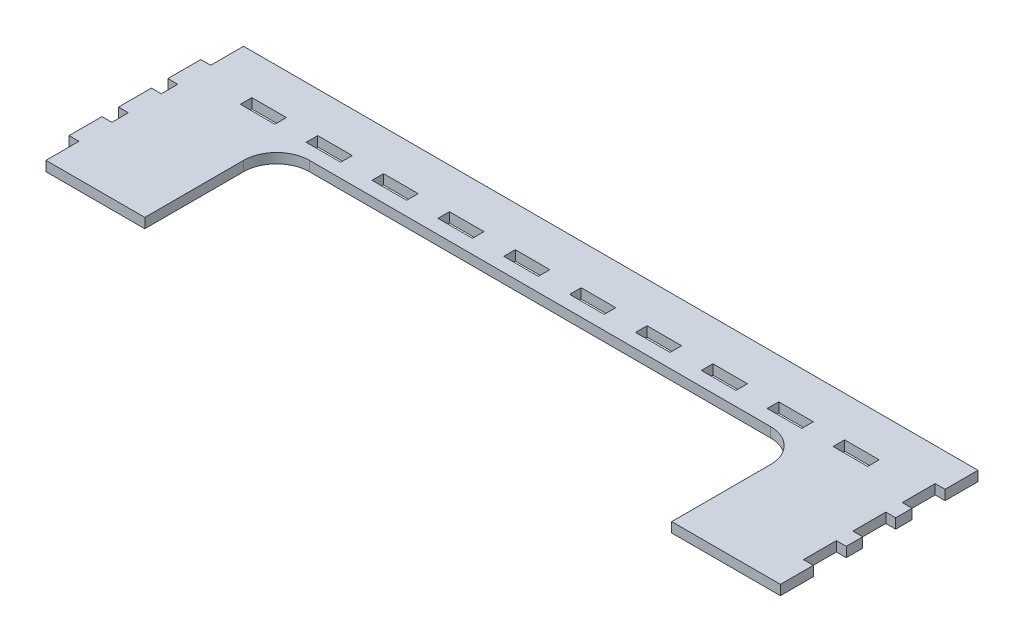
SolidWorks part; units mm, degrees
ref_plane "Спереди" through (0, 0, 0) normal (0, 0, 1) x (1, 0, 0)
ref_plane "Сверху" through (0, 0, 0) normal (0, 1, 0) x (1, 0, 0)
ref_plane "Справа" through (0, 0, 0) normal (1, 0, 0) x (0, 0, -1)
sketch "Эскиз1" plane through (0, 0, 0) normal (0, 1, 0) x (1, 0, 0)
  line L0 (-135, -31.7889) -> (-138, -31.7889)
  line L1 (45, -16.7889) -> (-95, -16.7889)
  line L3 (75, 3.2111) -> (-125, 3.2111)
  line L4 (-138, -31.7889) -> (-138, -21.7889)
  line L5 (-135, -56.7889) -> (-105, -56.7889)
  line L6 (-105, -56.7889) -> (-105, -26.7889)
  line L7 (-25, -16.7889) -> (-25, 56.3847) construction
  line L8 (85, -56.7889) -> (55, -56.7889)
  line L9 (55, -56.7889) -> (55, -26.7889)
  line L10 (88, -31.7889) -> (88, -36.7889)
  line L11 (-138, -21.7889) -> (-135, -21.7889)
  line L12 (-135, 3.2111) -> (-125, 3.2111)
  line L13 (88, -16.7889) -> (88, -21.7889)
  line L14 (85, 3.2111) -> (75, 3.2111)
  line L15 (-135, -46.7889) -> (-138, -46.7889)
  line L16 (-138, -46.7889) -> (-138, -36.7889)
  line L17 (-138, -36.7889) -> (-135, -36.7889)
  line L18 (-135, -46.7889) -> (-135, -56.7889)
  line L19 (-135, -16.7889) -> (-138, -16.7889)
  line L20 (-138, -16.7889) -> (-138, -6.7889)
  line L21 (-138, -6.7889) -> (-135, -6.7889)
  line L22 (-135, 3.2111) -> (-135, -6.7889)
  line L23 (-135, -16.7889) -> (-135, -21.7889)
  line L24 (-135, -31.7889) -> (-135, -36.7889)
  line L25 (88, -6.7889) -> (85, -6.7889)
  line L26 (85, -21.7889) -> (85, -31.7889)
  line L27 (85, -16.7889) -> (88, -16.7889)
  line L29 (88, -36.7889) -> (85, -36.7889)
  line L31 (85, -46.7889) -> (88, -46.7889)
  line L32 (88, -21.7889) -> (85, -21.7889)
  line L33 (85, -36.7889) -> (85, -46.7889)
  line L34 (85, -31.7889) -> (88, -31.7889)
  line L35 (85, 3.2111) -> (88, 3.2111)
  line L36 (88, 3.2111) -> (88, -6.7889)
  line L37 (85, -6.7889) -> (85, -16.7889)
  line L38 (88, -46.7889) -> (88, -56.7889)
  line L39 (88, -56.7889) -> (85, -56.7889)
  arc A2 (55, -26.7889) -> (45, -16.7889) centre (45, -26.7889) ccw
  arc A3 (-95, -16.7889) -> (-105, -26.7889) centre (-95, -26.7889) ccw
  point P0 (0, 0)
  point P16 (85, 3.2111)
  point P19 (-135, 3.2111)
  point P22 (55, -16.7889)
  point P25 (-105, -16.7889)
  dimension "D5" = 3
  dimension "D6" = 10
  dimension "D1" = 220
  dimension "D2" = 60
  dimension "D3" = 3
  dimension "D4" = 30
  dimension "D7" = 10
  dimension "D8" = 10
extrude "Бобышка-Вытянуть1" add sketch "Эскиз1" along normal blind 3
sketch "Эскиз2" plane through (0, 0, 0) normal (0, 1, 0) x (1, 0, 0)
  line L0 (-95, -16.7889) -> (45, -16.7889) construction
  line L1 (-105, -10.7889) -> (-44.1885, -10.7889) construction
  line L3 (-120.25, -12.5389) -> (-109.75, -12.5389)
  line L4 (-120.25, -12.5389) -> (-120.25, -9.0389)
  line L5 (-120.25, -9.0389) -> (-109.75, -9.0389)
  line L6 (-109.75, -12.5389) -> (-109.75, -9.0389)
  line L7 (-120.25, -12.5389) -> (-109.75, -9.0389) construction
  line L8 (-120.25, -9.0389) -> (-109.75, -12.5389) construction
  line L10 (-100.25, -9.0389) -> (-89.75, -9.0389)
  line L11 (-100.25, -12.5389) -> (-100.25, -9.0389)
  line L12 (-100.25, -12.5389) -> (-89.75, -12.5389)
  line L13 (-89.75, -12.5389) -> (-89.75, -9.0389)
  line L14 (-80.25, -9.0389) -> (-69.75, -9.0389)
  line L15 (-80.25, -12.5389) -> (-80.25, -9.0389)
  line L16 (-80.25, -12.5389) -> (-69.75, -12.5389)
  line L17 (-69.75, -12.5389) -> (-69.75, -9.0389)
  line L18 (-60.25, -9.0389) -> (-49.75, -9.0389)
  line L19 (-60.25, -12.5389) -> (-60.25, -9.0389)
  line L20 (-60.25, -12.5389) -> (-49.75, -12.5389)
  line L21 (-49.75, -12.5389) -> (-49.75, -9.0389)
  line L22 (-40.25, -9.0389) -> (-29.75, -9.0389)
  line L23 (-40.25, -12.5389) -> (-40.25, -9.0389)
  line L24 (-40.25, -12.5389) -> (-29.75, -12.5389)
  line L25 (-29.75, -12.5389) -> (-29.75, -9.0389)
  line L26 (-20.25, -9.0389) -> (-9.75, -9.0389)
  line L27 (-20.25, -12.5389) -> (-20.25, -9.0389)
  line L28 (-20.25, -12.5389) -> (-9.75, -12.5389)
  line L29 (-9.75, -12.5389) -> (-9.75, -9.0389)
  line L30 (-0.25, -9.0389) -> (10.25, -9.0389)
  line L31 (-0.25, -12.5389) -> (-0.25, -9.0389)
  line L32 (-0.25, -12.5389) -> (10.25, -12.5389)
  line L33 (10.25, -12.5389) -> (10.25, -9.0389)
  line L34 (19.75, -9.0389) -> (30.25, -9.0389)
  line L35 (19.75, -12.5389) -> (19.75, -9.0389)
  line L36 (19.75, -12.5389) -> (30.25, -12.5389)
  line L37 (30.25, -12.5389) -> (30.25, -9.0389)
  line L38 (39.75, -9.0389) -> (50.25, -9.0389)
  line L39 (39.75, -12.5389) -> (39.75, -9.0389)
  line L40 (39.75, -12.5389) -> (50.25, -12.5389)
  line L41 (50.25, -12.5389) -> (50.25, -9.0389)
  line L42 (59.75, -9.0389) -> (70.25, -9.0389)
  line L43 (59.75, -12.5389) -> (59.75, -9.0389)
  line L44 (59.75, -12.5389) -> (70.25, -12.5389)
  line L45 (70.25, -12.5389) -> (70.25, -9.0389)
  point P0 (-105, -10.7889)
  point P4 (-115, -10.7889)
  dimension "D1" = 14.75
  dimension "D2" = 3.5
  dimension "D3" = 10.5
  dimension "D6" = 6
  dimension "D5" = 10
extrude "Вырез-Вытянуть1" cut sketch "Эскиз2" along normal through all
